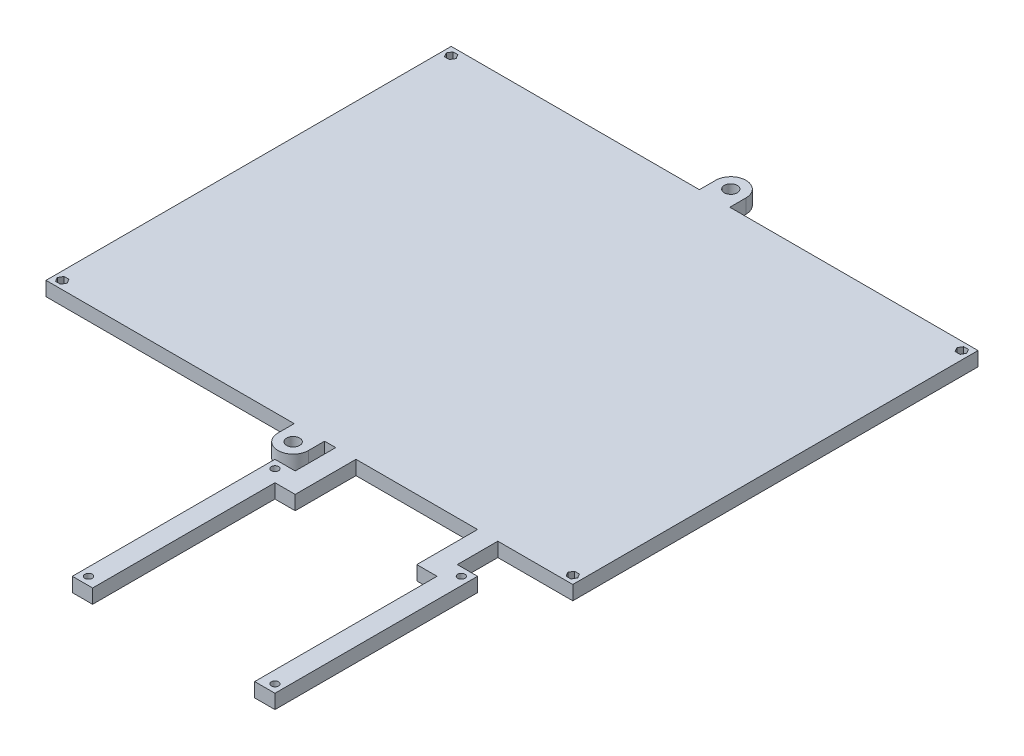
SolidWorks part; units mm, degrees
ref_plane "Front Plane" through (0, 0, 0) normal (0, 0, 1) x (1, 0, 0)
ref_plane "Top Plane" through (0, 0, 0) normal (0, 1, 0) x (1, 0, 0)
ref_plane "Right Plane" through (0, 0, 0) normal (1, 0, 0) x (0, 0, -1)
sketch "Sketch1" plane through (0, 0, 0) normal (0, 1, 0) x (1, 0, 0)
  line L0 (65, 0) -> (65, 4) construction
  line L1 (0, 0) -> (61.25, 0)
  line L2 (0, 0) -> (0, -100)
  line L3 (0, -100) -> (61.25, -100)
  line L4 (130, 0) -> (130, -100)
  line L5 (68.75, 0) -> (130, 0)
  line L7 (61.25, 4) -> (61.25, 0)
  line L9 (68.75, 4) -> (68.75, 0)
  line L10 (65, -100) -> (65, -104) construction
  line L11 (68.75, -100) -> (71.5, -100)
  line L13 (61.25, -104) -> (61.25, -100)
  line L15 (68.75, -104) -> (68.75, -100)
  line L16 (71.5, -110) -> (66.5, -110)
  line L18 (71.5, -100) -> (71.5, -110)
  line L20 (76.5, -100) -> (76.5, -110)
  line L22 (106.5, -100) -> (106.5, -110)
  line L24 (111.5, -100) -> (111.5, -110)
  line L25 (66.5, -110) -> (66.5, -160)
  line L26 (66.5, -160) -> (71.5, -160)
  line L27 (71.5, -160) -> (71.5, -115)
  line L28 (71.5, -115) -> (76.5, -115)
  line L29 (76.5, -115) -> (76.5, -110)
  line L30 (106.5, -110) -> (106.5, -115)
  line L31 (106.5, -115) -> (111.5, -115)
  line L32 (111.5, -115) -> (111.5, -160)
  line L33 (111.5, -160) -> (116.5, -160)
  line L34 (116.5, -160) -> (116.5, -110)
  line L35 (116.5, -110) -> (111.5, -110)
  line L36 (76.5, -100) -> (106.5, -100)
  line L37 (111.5, -100) -> (130, -100)
  line L38 (114.5, -110) -> (114.5, -112) construction
  line L39 (114.5, -112) -> (116.5, -112) construction
  line L41 (116.5, -160) -> (114.5, -160) construction
  line L42 (116.5, -160) -> (116.5, -158) construction
  line L43 (116.5, -158) -> (114.5, -158) construction
  line L44 (114.5, -160) -> (114.5, -158) construction
  line L45 (66.5, -160) -> (68.5, -160) construction
  line L46 (66.5, -160) -> (66.5, -158) construction
  line L47 (66.5, -158) -> (68.5, -158) construction
  line L48 (68.5, -160) -> (68.5, -158) construction
  line L49 (66.5, -110) -> (68.5, -110) construction
  line L50 (66.5, -110) -> (66.5, -112) construction
  line L51 (66.5, -112) -> (68.5, -112) construction
  line L52 (68.5, -110) -> (68.5, -112) construction
  arc A0 (68.75, 4) -> (61.25, 4) centre (65, 4) ccw
  circle A1 centre (65, 4) radius 1.6
  circle A2 centre (65, -104) radius 1.6
  arc A3 (61.25, -104) -> (68.75, -104) centre (65, -104) ccw
  circle A4 centre (114.5, -112) radius 0.9
  circle A5 centre (114.5, -158) radius 0.9
  circle A6 centre (68.5, -158) radius 0.9
  circle A7 centre (68.5, -112) radius 0.9
  dimension "D3" = 3.2
  dimension "D4" = 7.5
  dimension "D6" = 3.2
  dimension "D7" = 7.5
  dimension "D29" = 1.8
  dimension "D1" = 130
  dimension "D2" = 100
  dimension "D5" = 4
  dimension "D8" = 4
  dimension "D9" = 2.75
  dimension "D10" = 10
  dimension "D11" = 5
  dimension "D12" = 65
  dimension "D13" = 5
  dimension "D14" = 5
  dimension "D15" = 50
  dimension "D16" = 5
  dimension "D17" = 5
  dimension "D18" = 40
  dimension "D19" = 5
  dimension "D20" = 2
  dimension "D21" = 5
  dimension "D22" = 5
  dimension "D23" = 2
  dimension "D24" = 2
  dimension "D25" = 2
  dimension "D26" = 2
  dimension "D27" = 2
  dimension "D28" = 2
extrude "Boss-Extrude1" add sketch "Sketch1" along normal blind 3.5
sketch "Sketch2" plane through (0, 3.5, 0) normal (0, 1, 0) x (1, 0, 0)
  line L0 (130, -100) -> (130, 0) construction
  line L1 (2, -2) -> (128, -2) construction
  line L2 (2, -2) -> (2, -98) construction
  line L3 (2, -98) -> (128, -98) construction
  line L4 (128, -2) -> (128, -98) construction
  line L5 (130, 0) -> (68.75, 0) construction
  line L6 (0, 0) -> (0, -100) construction
  line L7 (0, -100) -> (61.25, -100) construction
  line L9 (3.2124, -2) -> (2.6062, -0.95)
  line L10 (2.6062, -0.95) -> (1.3938, -0.95)
  line L11 (1.3938, -0.95) -> (0.7876, -2)
  line L12 (0.7876, -2) -> (1.3938, -3.05)
  line L13 (1.3938, -3.05) -> (2.6062, -3.05)
  line L14 (2.6062, -3.05) -> (3.2124, -2)
  line L15 (126.7876, -2) -> (127.3938, -3.05)
  line L16 (127.3938, -3.05) -> (128.6062, -3.05)
  line L17 (128.6062, -3.05) -> (129.2124, -2)
  line L18 (129.2124, -2) -> (128.6062, -0.95)
  line L19 (128.6062, -0.95) -> (127.3938, -0.95)
  line L20 (127.3938, -0.95) -> (126.7876, -2)
  line L21 (126.7876, -98) -> (127.3938, -99.05)
  line L22 (127.3938, -99.05) -> (128.6062, -99.05)
  line L23 (128.6062, -99.05) -> (129.2124, -98)
  line L24 (129.2124, -98) -> (128.6062, -96.95)
  line L25 (128.6062, -96.95) -> (127.3938, -96.95)
  line L26 (127.3938, -96.95) -> (126.7876, -98)
  line L27 (3.2124, -98) -> (2.6062, -96.95)
  line L28 (2.6062, -96.95) -> (1.3938, -96.95)
  line L29 (1.3938, -96.95) -> (0.7876, -98)
  line L30 (0.7876, -98) -> (1.3938, -99.05)
  line L31 (1.3938, -99.05) -> (2.6062, -99.05)
  line L32 (2.6062, -99.05) -> (3.2124, -98)
  circle A0 centre (2, -2) radius 1.05 construction
  circle A1 centre (128, -2) radius 1.05 construction
  circle A2 centre (128, -98) radius 1.05 construction
  circle A3 centre (2, -98) radius 1.05 construction
  dimension "D5" = 2.1
  dimension "D1" = 2
  dimension "D2" = 2
  dimension "D3" = 2
  dimension "D4" = 2
extrude "Cut-Extrude1" cut sketch "Sketch2" against normal blind 2.3
